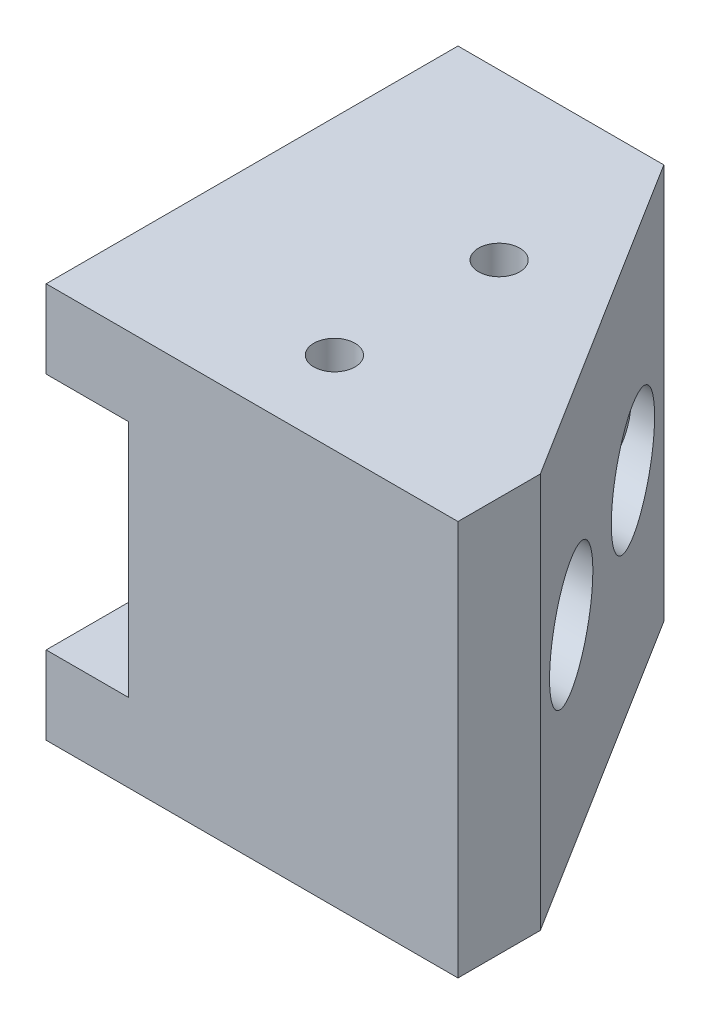
SolidWorks part; units mm, degrees
ref_plane "Front" through (0, 0, 0) normal (0, 0, 1) x (1, 0, 0)
ref_plane "Top" through (0, 0, 0) normal (0, 1, 0) x (1, 0, 0)
ref_plane "Right" through (0, 0, 0) normal (1, 0, 0) x (0, 0, -1)
sketch "草图1" plane through (0, 0, 0) normal (1, 0, 0) x (0, 0, -1)
  line L1 (12.5, -12) -> (-12.5, -12)
  line L2 (12.5, -12) -> (12.5, 12)
  line L3 (12.5, 12) -> (-12.5, 12)
  line L4 (-12.5, -12) -> (-12.5, 12)
  line L5 (12.5, -12) -> (-12.5, 12) construction
  line L6 (12.5, 12) -> (-12.5, -12) construction
  point P0 (0, 0)
  dimension "D1" = 25
  dimension "D2" = 24
extrude "凸台-拉伸1" add sketch "草图1" along normal blind 25
sketch "草图2" plane through (0, 0, 0) normal (-1, 0, 0) x (0, 0, 1)
  line L0 (-12.5, -12) -> (-12.5, 12) construction
  line L1 (12.5, -7.25) -> (-12.5, -7.25)
  line L2 (12.5, -7.25) -> (12.5, 7.25)
  line L3 (12.5, 7.25) -> (-12.5, 7.25)
  line L4 (-12.5, -7.25) -> (-12.5, 7.25)
  line L5 (12.5, -7.25) -> (-12.5, 7.25) construction
  line L6 (12.5, 7.25) -> (-12.5, -7.25) construction
  point P0 (0, 0)
  dimension "D1" = 14.5
extrude "切除-拉伸1" cut sketch "草图2" against normal blind 5
sketch "草图3" plane through (25, 0, 0) normal (1, 0, 0) x (0, 0, -1)
  line L0 (-12.5, 0) -> (12.5, 0) construction
  line L1 (-12.5, 12) -> (-12.5, -12) construction
  line L2 (12.5, -12) -> (12.5, 12) construction
  line L3 (2.5, 12) -> (2.5, -12) construction
  circle A0 centre (-2.5, 0) radius 1.5
  circle A1 centre (7.5, 0) radius 1.5
  point P10 (0, 0)
  point P16 (0, 0)
  point P17 (0, 0)
  point P18 (0, 0)
  dimension "D1" = 3
  dimension "D2" = 3
  dimension "D3" = 10
  dimension "D4" = 10
extrude "切除-拉伸2" cut sketch "草图3" against normal through all
sketch "草图5" plane through (0, 12, 0) normal (0, 1, 0) x (1, 0, 0)
  line L0 (12.5, 12.5) -> (25, -7.5)
  line L1 (25, 12.5) -> (0, 12.5) construction
  line L2 (25, 12.5) -> (25, -12.5) construction
  line L3 (25, -7.5) -> (25, 12.5)
  line L4 (25, 12.5) -> (12.5, 12.5)
  line L5 (0, 12.5) -> (0, -12.5) construction
  line L6 (25, -12.5) -> (0, -12.5) construction
  point P9 (0, 0)
  point P13 (25, -7.0102)
  dimension "D1" = 12.5
  dimension "D2" = 5
extrude "切除-拉伸3" cut sketch "草图5" against normal through all
sketch "草图6" plane through (25, 0, 0) normal (1, 0, 0) x (0, 0, -1)
  circle A0 centre (7.5, 0) radius 3.5
  circle A1 centre (7.5, 0) radius 1.5 construction
  dimension "D1" = 7
extrude "切除-拉伸4" cut sketch "草图6" against normal blind 13
sketch "草图7" plane through (25, 0, 0) normal (1, 0, 0) x (0, 0, -1)
  circle A0 centre (-2.5, 0) radius 3.5
  circle A1 centre (-2.5, 0) radius 1.5 construction
  dimension "D1" = 7
extrude "切除-拉伸5" cut sketch "草图7" against normal blind 7
sketch "草图8" plane through (0, 12, 0) normal (0, 1, 0) x (1, 0, 0)
  line L0 (12.5, 12.5) -> (12.5, -12.5) construction
  line L1 (25, -12.5) -> (0, -12.5) construction
  circle A0 centre (12.5, 2.5) radius 1.25
  circle A1 centre (12.5, -7.5) radius 1.25
  point P9 (12.5, -7.5)
  point P11 (0, 0)
  dimension "D1" = 2.5
  dimension "D2" = 2.5
  dimension "D3" = 5
  dimension "D4" = 15
extrude "切除-拉伸6" cut sketch "草图8" against normal through all
